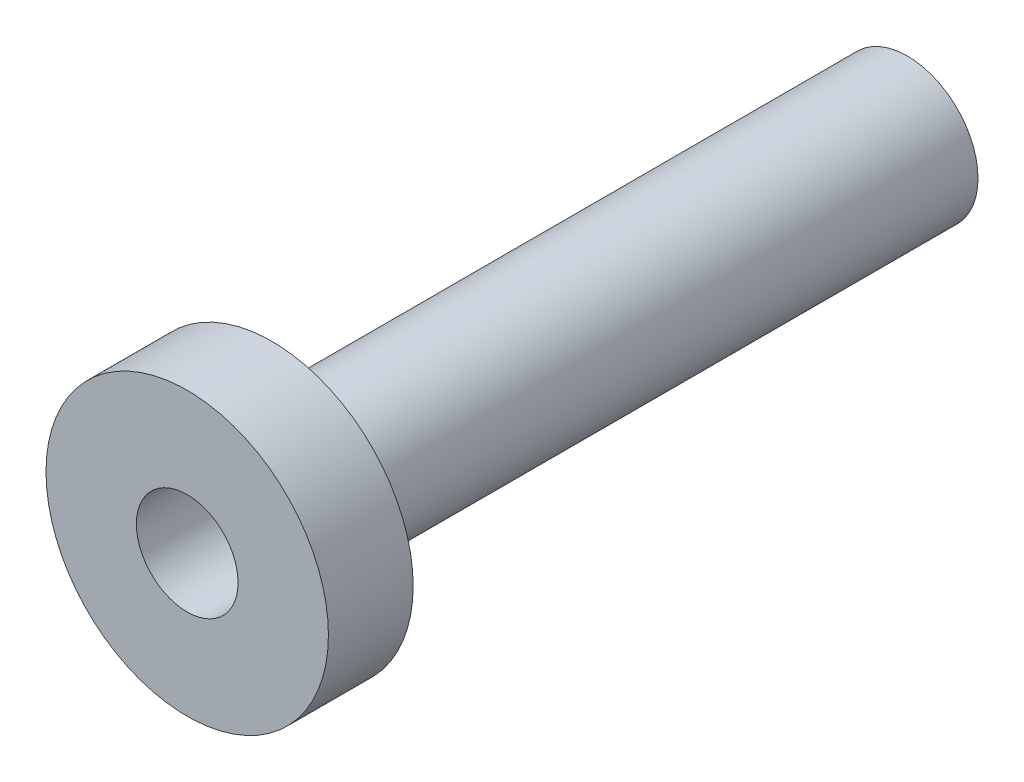
SolidWorks part; units mm, degrees
ref_plane "Alzado" through (0, 0, 0) normal (0, 0, 1) x (1, 0, 0)
ref_plane "Planta" through (0, 0, 0) normal (0, 1, 0) x (1, 0, 0)
ref_plane "Vista lateral" through (0, 0, 0) normal (1, 0, 0) x (0, 0, -1)
sketch "Croquis1" plane through (0, 0, 0) normal (0, 0, 1) x (1, 0, 0)
  circle A0 centre (0, 0) radius 1.8
  circle A1 centre (0, 0) radius 2.5
  dimension "D1" = 3.6
  dimension "D2" = 5
extrude "Saliente-Extruir1" add sketch "Croquis1" along normal blind 24
sketch "Croquis2" plane through (0, 0, 24) normal (0, 0, 1) x (1, 0, 0)
  line L0 (-1.8, 0) -> (1.8, 0) construction
  line L1 (0, -1.8) -> (0, 1.8) construction
  circle A0 centre (0, 0) radius 1.8 construction
  point P8 (0, 0)
  point P13 (0, 0)
sketch "Croquis3" plane through (0, 0, 0) normal (0, 0, -1) x (-1, 0, 0)
  circle A0 centre (0, 0) radius 1.8
extrude "Saliente-Extruir2" add sketch "Croquis3" against normal blind 3.15
sketch "Croquis4" plane through (0, 0, 0) normal (0, 0, -1) x (-1, 0, 0)
  line L0 (0, -1.8) -> (0, 1.8) construction
  circle A0 centre (0, 0) radius 1.265
  dimension "D1" = 2.53
extrude "Cortar-Extruir1" cut sketch "Croquis4" against normal through all both and the other way through all
sketch "Croquis5" plane through (0, 0, 24) normal (0, 0, 1) x (1, 0, 0)
  circle A0 centre (0, 0) radius 1.8
  circle A1 centre (0, 0) radius 5
  point P0 (0, 0)
  dimension "D3" = 3.6
  dimension "D1" = 10
extrude "Saliente-Extruir3" add sketch "Croquis5" along normal mid plane 3
